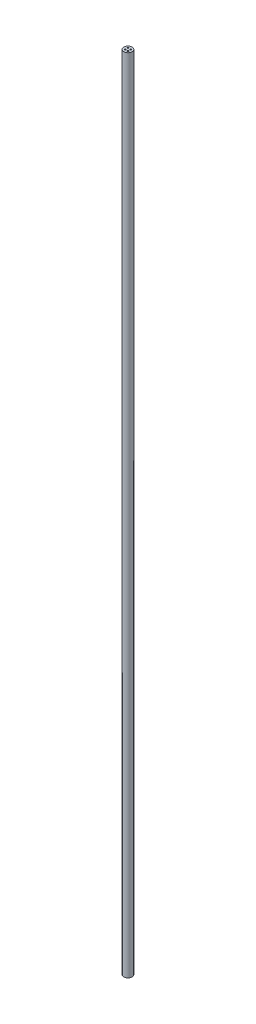
SolidWorks part; units mm, degrees
ref_plane "Front Plane" through (0, 0, 0) normal (0, 0, 1) x (1, 0, 0)
ref_plane "Top Plane" through (0, 0, 0) normal (0, 1, 0) x (1, 0, 0)
ref_plane "Right Plane" through (0, 0, 0) normal (1, 0, 0) x (0, 0, -1)
sketch "Sketch1" plane through (0, 0, 0) normal (0, 1, 0) x (1, 0, 0)
  circle A0 centre (0, 0) radius 0.7874
  circle A1 centre (-0.254, 0.254) radius 0.127
  circle A2 centre (0.254, 0.254) radius 0.127
  circle A3 centre (-0.254, -0.254) radius 0.127
  circle A4 centre (0.254, -0.254) radius 0.127
  dimension "D1" = 1.5748
  dimension "D2" = 0.254
  dimension "D3" = 0.254
  dimension "D4" = 0.254
  dimension "D5" = 0.254
  dimension "D6" = 0.508
  dimension "D7" = 0.508
  dimension "D8" = 0.254
  dimension "D9" = 0.254
  dimension "D10" = 0.254
  dimension "D11" = 0.254
  dimension "D12" = 0.254
  dimension "D13" = 0.254
extrude "Boss-Extrude1" add sketch "Sketch1" against normal blind 152.4
sketch "Sketch2" plane through (0, -152.4, 0) normal (0, -1, 0) x (-1, 0, 0)
  circle A0 centre (0, 0) radius 0.6392
